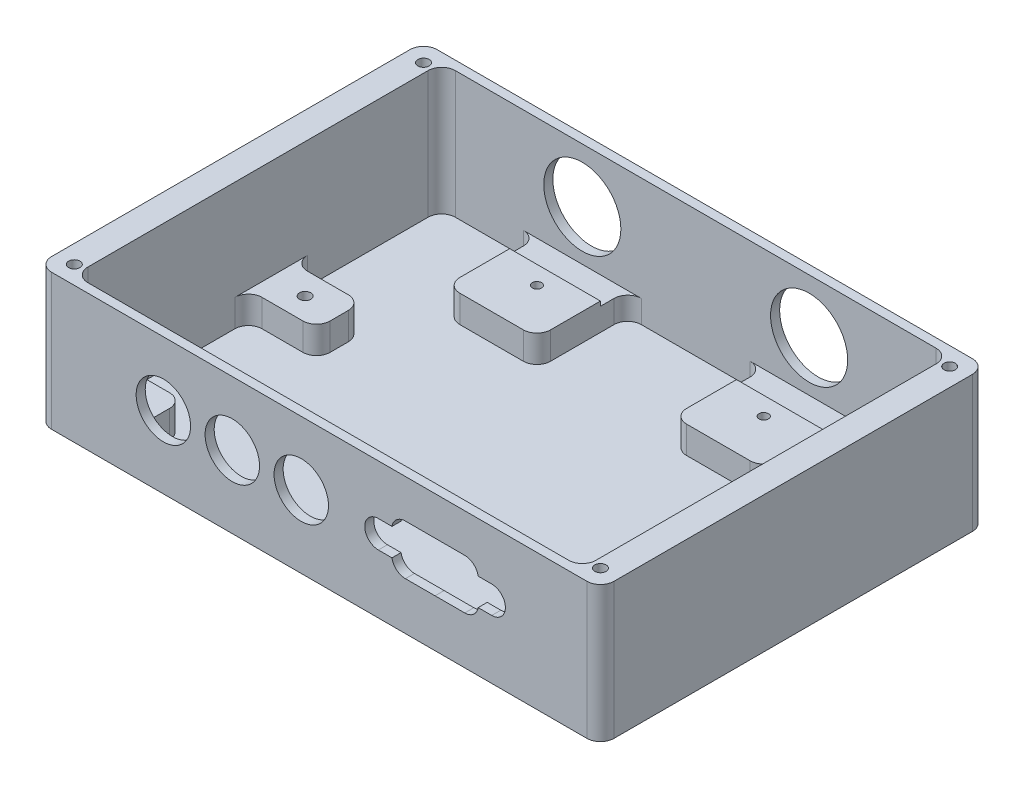
SolidWorks part; units mm, degrees
ref_plane "Ebene vorne" through (0, 0, 0) normal (0, 0, 1) x (1, 0, 0)
ref_plane "Ebene oben" through (0, 0, 0) normal (0, 1, 0) x (1, 0, 0)
ref_plane "Ebene rechts" through (0, 0, 0) normal (1, 0, 0) x (0, 0, -1)
sketch "Skizze1" plane through (0, 0, 0) normal (0, 1, 0) x (1, 0, 0)
  line L1 (0, 0) -> (116, 0)
  line L2 (0, 0) -> (0, 85)
  line L3 (0, 85) -> (116, 85)
  line L4 (116, 0) -> (116, 85)
  dimension "D1" = 85
  dimension "D2" = 116
extrude "Aufsatz-Linear austragen1" add sketch "Skizze1" along normal blind 30
shell "Schale1" thickness 2
sketch "Skizze2" plane through (0, 0, 0) normal (0, 0, 1) x (1, 0, 0)
  line L0 (4.8493, 15.94) -> (121.4088, 15.94) construction
  line L1 (0, 0) -> (116, 0) construction
  line L2 (0, 30) -> (0, 0) construction
  circle A0 centre (23.64, 15.94) radius 6
  circle A1 centre (38.84, 15.94) radius 6
  circle A2 centre (54.04, 15.94) radius 6
  dimension "D2" = 12
  dimension "D3" = 23.64
  dimension "D4" = 38.84
  dimension "D5" = 54.04
  dimension "D8" = 12
  dimension "D9" = 12
  dimension "D1" = 15.94
extrude "Schnitt-Linear austragen1" cut sketch "Skizze2" against normal blind 30
sketch "Skizze3" plane through (0, 0, 0) normal (0, 0, 1) x (1, 0, 0)
  line L0 (83.5402, 21.49) -> (76.9981, 21.49)
  line L1 (74.0401, 18.99) -> (71.04, 18.99)
  line L2 (0, 30) -> (0, 0) construction
  line L3 (68.04, 15.99) -> (134.747, 15.99) construction
  line L5 (83.5399, 11.9127) -> (83.5402, 21.49) construction
  line L7 (83.5402, 10.49) -> (76.9981, 10.49)
  line L8 (74.0401, 12.99) -> (71.04, 12.99)
  line L9 (83.5395, 10.49) -> (90.0816, 10.4896)
  line L10 (83.5402, 21.49) -> (90.0822, 21.4896)
  line L11 (93.0398, 12.9895) -> (96.0398, 12.9893)
  line L12 (93.0401, 18.9895) -> (96.0402, 18.9893)
  arc A0 (76.9981, 21.49) -> (74.0401, 18.99) centre (76.9981, 18.49) ccw
  arc A1 (71.04, 18.99) -> (71.04, 12.99) centre (71.04, 15.99) ccw
  arc A2 (76.9981, 10.49) -> (74.0401, 12.99) centre (76.9981, 13.49) cw
  arc A3 (90.0816, 10.4896) -> (93.0398, 12.9895) centre (90.0817, 13.4896) ccw
  arc A4 (96.0402, 18.9893) -> (96.0398, 12.9893) centre (96.04, 15.9893) cw
  arc A5 (90.0822, 21.4896) -> (93.0401, 18.9895) centre (90.082, 18.4896) cw
  point P12 (68.04, 15.99)
  dimension "D7" = 3
  dimension "D1" = 5.5
  dimension "D2" = 9.5
  dimension "D3" = 3
  dimension "D4" = 15.99
  dimension "D5" = 68.04
  dimension "D6" = 15.5
extrude "Schnitt-Linear austragen2" cut sketch "Skizze3" against normal blind 10 contours A5 L10 L0 A0 L1 A1 L8 A2 L7 L9 A3 L11 A4 L12
fillet "Verrundung1" radius 3 8 edges at (0, 15, -85) (116, 15, -85) (116, 15, 0) (0, 15, 0) (114, 16, -2) (114, 16, -83) (2, 16, -83) (2, 16, -2)
sketch "Skizze4" plane through (0, 2, 0) normal (0, 1, 0) x (1, 0, 0)
  line L0 (2, 12) -> (13, 12)
  line L1 (2, 80) -> (2, 5) construction
  line L2 (16, 9) -> (16, 2)
  line L3 (5, 2) -> (111, 2) construction
  line L5 (5, 2) -> (16, 2)
  line L6 (2, 12) -> (2, 5)
  line L7 (58, 0) -> (58, 20.7722) construction
  line L8 (3, 0) -> (113, 0) construction
  line L9 (114, 12) -> (114, 5)
  line L10 (111, 2) -> (100, 2)
  line L11 (100, 9) -> (100, 2)
  line L12 (114, 12) -> (103, 12)
  arc A1 (13, 12) -> (16, 9) centre (13, 9) cw
  arc A2 (2, 5) -> (5, 2) centre (5, 5) ccw construction
  arc A3 (2, 5) -> (5, 2) centre (5, 5) ccw
  arc A4 (114, 5) -> (111, 2) centre (111, 5) cw
  arc A5 (103, 12) -> (100, 9) centre (103, 9) ccw
  point P13 (16, 12)
  line M4 (5, 2) -> (111, 2)
  arc M5 (111, 2) -> (114, 5) centre (111, 5) ccw
  line M6 (114, 5) -> (114, 80)
  line M10 (2, 80) -> (2, 5)
  arc M11 (2, 5) -> (5, 2) centre (5, 5) ccw
  dimension "D5" = 3
  dimension "D3" = 14
  dimension "D4" = 10
extrude "Aufsatz-Linear austragen2" add sketch "Skizze4" along normal blind 6 contours A1 L0 L2 M10 M11 M4 | L12 A5 L11 M4 M5 M6
fillet "Verrundung2" radius 3 4 edges at (114, 5, -12) (100, 5, -2) (16, 5, -2) (2, 5, -12)
sketch "Skizze5" plane through (0, 2, 0) normal (0, 1, 0) x (1, 0, 0)
  line L0 (2, 80) -> (2, 5) construction
  line L1 (2, 50.4) -> (17, 50.4)
  line L2 (2, 50.4) -> (2, 40.4)
  line L3 (2, 40.4) -> (17, 40.4)
  line L4 (17, 50.4) -> (17, 40.4)
  line L5 (16, 7) -> (7.9271, 7) construction
  line L6 (16, 9) -> (16, 5) construction
  line L7 (17, 45.4) -> (7.9271, 45.4) construction
  line L8 (58, 0) -> (58, 60.7015) construction
  line L9 (3, 0) -> (113, 0) construction
  line L10 (99, 50.4) -> (99, 40.4)
  line L11 (114, 40.4) -> (99, 40.4)
  line L12 (114, 50.4) -> (114, 40.4)
  line L13 (114, 50.4) -> (99, 50.4)
  dimension "D1" = 38.4
  dimension "D2" = 10
  dimension "D3" = 15
extrude "Aufsatz-Linear austragen3" add sketch "Skizze5" along normal blind 6
fillet "Verrundung3" radius 3 8 edges at (114, 5, -40.4) (114, 5, -50.4) (99, 5, -40.4) (99, 5, -50.4) (2, 5, -50.4) (17, 5, -50.4) (17, 5, -40.4) (2, 5, -40.4)
sketch "Skizze6" plane through (0, 0, -85) normal (0, 0, -1) x (-1, 0, 0)
  line L0 (-128.5127, 18) -> (-8.2871, 18) construction
  line L1 (-113, 0) -> (-3, 0) construction
  line L2 (-58, 0) -> (-58, 33.8667) construction
  circle A0 centre (-83, 18) radius 8.5
  circle A1 centre (-33, 18) radius 8.5
  dimension "D2" = 17
  dimension "D3" = 50
  dimension "D1" = 18
extrude "Schnitt-Linear austragen3" cut sketch "Skizze6" against normal blind 5
sketch "Skizze7" plane through (0, 2, 0) normal (0, 1, 0) x (1, 0, 0)
  line L0 (58, 85) -> (58, 35.1088) construction
  line L1 (113, 85) -> (3, 85) construction
  line L2 (111, 83) -> (5, 83) construction
  line L3 (23, 63) -> (43, 63)
  line L4 (23, 63) -> (23, 83)
  line L5 (23, 83) -> (43, 83)
  line L6 (43, 63) -> (43, 83)
  line L7 (33, 63) -> (33, 71.5986) construction
  line L8 (0, 82) -> (0, 3) construction
  line L9 (23, 63) -> (23, 83)
  line L10 (43, 63) -> (43, 83)
  line L11 (93, 83) -> (73, 83)
  line L12 (73, 63) -> (73, 83)
  line L13 (93, 63) -> (73, 63)
  line L14 (93, 63) -> (93, 83)
  line M17 (111, 83) -> (5, 83)
  dimension "D1" = 33
  dimension "D2" = 20
  dimension "D3" = 20
extrude "Aufsatz-Linear austragen4" add sketch "Skizze7" along normal blind 6 contours L3 L6 L4 M17 | L13 L14 L12 M17
fillet "Verrundung4" radius 3 8 edges at (93, 5, -83) (93, 5, -63) (73, 5, -63) (73, 5, -83) (23, 5, -83) (23, 5, -63) (43, 5, -83) (43, 5, -63)
hole_wizard "M3 Gewindebohrung1" positions "Skizze8" profile "Skizze9" tap size "M3" standard "DIN"
sketch "Skizze8" plane through (0, 8, 0) normal (0, 1, 0) x (1, 0, 0)
  line L1 (106.5, 7.4) -> (9.5, 7.4) construction
  line L2 (106.5, 7.4) -> (106.5, 45.4) construction
  line L3 (106.5, 45.4) -> (9.5, 45.4) construction
  line L4 (9.5, 7.4) -> (9.5, 45.4) construction
  line L5 (19, 2) -> (97, 2) construction
  line L6 (114, 15) -> (114, 37.4) construction
  line L7 (58, 0) -> (58, 59.3993) construction
  line L8 (3, 0) -> (113, 0) construction
  point P1 (106.5, 7.4)
  point P2 (9.5, 45.4)
  point P117 (106.5, 45.4)
  point P118 (9.5, 7.4)
  dimension "D1" = 5.4
  dimension "D2" = 7.5
  dimension "D3" = 38
  dimension "D4" = 97
sketch "Skizze9" plane through (106.5, 8, -7.4) normal (1, 0, 0) x (0, 0, 1)
  line L0 (0, 0) -> (0, 9.2511)
  line L1 (0, 9.2511) -> (1.25, 8.5)
  line L2 (1.25, 8.5) -> (1.25, 0)
  line L5 (1.25, 0) -> (0, 0)
  line L10 (0, 9.2511) -> (-1.25, 8.5) construction
  line L11 (0, -6.35) -> (0, 107.95) construction
  dimension "Bohrerdurchmesser" = 2.5
  dimension "Bohrungstiefe" = 8.5
  dimension "Spitzenwinkel" = 118
cosmetic thread "Bohrungsgewinde4" parameters "D1"=6, "D2"=3
cosmetic thread "Bohrungsgewinde7" parameters "D1"=6, "D2"=3
cosmetic thread "Bohrungsgewinde9" parameters "D1"=6, "D2"=3
cosmetic thread "Bohrungsgewinde10" parameters "D1"=6, "D2"=3
hole_wizard "M2.5 Gewindebohrung1" positions "Skizze10" profile "Skizze11" tap size "M2.5" standard "DIN"
sketch "Skizze10" plane through (0, 8, 0) normal (0, 1, 0) x (1, 0, 0)
  line L0 (83, 63) -> (83, 83) construction
  line L1 (90, 63) -> (76, 63) construction
  line L2 (33, 63) -> (33, 83) construction
  line L3 (26, 63) -> (40, 63) construction
  line L4 (96, 83) -> (70, 83) construction
  point P10 (83, 73)
  point P12 (33, 73)
  dimension "D1" = 10
sketch "Skizze11" plane through (33, 8, -73) normal (1, 0, 0) x (0, 0, 1)
  line L0 (0, 0) -> (0, 7.8659)
  line L1 (0, 7.8659) -> (1.025, 7.25)
  line L2 (1.025, 7.25) -> (1.025, 0)
  line L5 (1.025, 0) -> (0, 0)
  line L10 (0, 7.8659) -> (-1.025, 7.25) construction
  line L11 (0, -6.35) -> (0, 107.95) construction
  dimension "Bohrerdurchmesser" = 2.05
  dimension "Bohrungstiefe" = 7.25
  dimension "Spitzenwinkel" = 118
cosmetic thread "Bohrungsgewinde5" parameters "D1"=5, "D2"=2.5
cosmetic thread "Bohrungsgewinde6" parameters "D1"=5, "D2"=2.5
sketch "Skizze12" plane through (0, 8, 0) normal (0, 1, 0) x (1, 0, 0)
  line L0 (111, 83) -> (96, 83) construction
  line L1 (108.8489, 83) -> (18.8489, 83)
  line L2 (108.8489, 83) -> (108.8489, 77)
  line L3 (108.8489, 77) -> (18.8489, 77)
  line L4 (18.8489, 83) -> (18.8489, 77)
  dimension "D1" = 6
  dimension "D2" = 90
extrude "Schnitt-Linear austragen4" cut sketch "Skizze12" against normal blind 1
sketch "Skizze13" plane through (0, 2, 0) normal (0, 1, 0) x (1, 0, 0)
  line L0 (119.1739, 25) -> (-5.709, 25) construction
  line L1 (58, 0) -> (58, 42.5667) construction
  line L2 (3, 0) -> (113, 0) construction
  circle A0 centre (88, 25) radius 3.2
  circle A1 centre (28, 25) radius 3.2
  dimension "D2" = 6.4
  dimension "D3" = 30
  dimension "D1" = 25
extrude "Schnitt-Linear austragen5" cut sketch "Skizze13" against normal blind 10
sketch "Skizze14" plane through (0, 0, 0) normal (0, -1, 0) x (-1, 0, 0)
  line L0 (-116, 3) -> (-116, 82) construction
  line L1 (-116, 0) -> (-120, 0)
  line L2 (-116, 3) -> (-116, 82)
  line L3 (-116, 85) -> (-120, 85)
  line L4 (-120, 0) -> (-120, 85)
  line L5 (0, 85) -> (4, 85)
  line L6 (0, 82) -> (0, 3)
  line L7 (0, 0) -> (4, 0)
  line L8 (4, 85) -> (4, 0)
  line L9 (0, 82) -> (0, 3) construction
  line L10 (-113, 85) -> (-116, 85)
  line L11 (-113, 0) -> (-116, 0)
  line L12 (-3, 0) -> (-113, 0) construction
  line L13 (0, 85) -> (-3, 85)
  line L14 (0, 0) -> (-3, 0)
  arc A0 (-113, 85) -> (-116, 82) centre (-113, 82) ccw
  arc A1 (-116, 3) -> (-113, 0) centre (-113, 3) ccw
  arc A2 (-3, 0) -> (0, 3) centre (-3, 3) ccw
  arc A3 (-3, 0) -> (0, 3) centre (-3, 3) ccw construction
  arc A4 (-3, 85) -> (0, 82) centre (-3, 82) cw
  arc A5 (0, 82) -> (-3, 85) centre (-3, 82) ccw construction
  dimension "D1" = 4
  dimension "D2" = 4
extrude "Aufsatz-Linear austragen5" add sketch "Skizze14" against normal up to surface (30 mm away) up to face at (58, 30, -42.5)
fillet "Verrundung5" radius 3 4 edges at (-4, 15, -85) (-4, 15, 0) (120, 15, -85) (120, 15, 0)
hole_wizard "M3 Gewindebohrung2" positions "Skizze15" profile "Skizze16" tap size "M3" standard "DIN"
sketch "Skizze15" plane through (0, 30, 0) normal (0, 1, 0) x (1, 0, 0)
  line L1 (0, 4) -> (116, 4) construction
  line L2 (0, 4) -> (0, 81) construction
  line L3 (0, 81) -> (116, 81) construction
  line L4 (116, 4) -> (116, 81) construction
  line L5 (117, 85) -> (-1, 85) construction
  line L6 (-1, 0) -> (117, 0) construction
  line L7 (120, 3) -> (120, 82) construction
  line L8 (-4, 82) -> (-4, 3) construction
  point P0 (0, 4)
  point P1 (116, 81)
  point P106 (0, 81)
  point P107 (116, 4)
  dimension "D1" = 4
  dimension "D2" = 4
  dimension "D3" = 4
  dimension "D4" = 4
sketch "Skizze16" plane through (0, 30, -4) normal (1, 0, 0) x (0, 0, 1)
  line L0 (0, 0) -> (0, 9.2511)
  line L1 (0, 9.2511) -> (1.25, 8.5)
  line L2 (1.25, 8.5) -> (1.25, 0)
  line L5 (1.25, 0) -> (0, 0)
  line L10 (0, 9.2511) -> (-1.25, 8.5) construction
  line L11 (0, -6.35) -> (0, 107.95) construction
  dimension "Bohrerdurchmesser" = 2.5
  dimension "Bohrungstiefe" = 8.5
  dimension "Spitzenwinkel" = 118
cosmetic thread "Bohrungsgewinde11" parameters "D1"=6, "D2"=3
cosmetic thread "Bohrungsgewinde12" parameters "D1"=6, "D2"=3
cosmetic thread "Bohrungsgewinde13" parameters "D1"=6, "D2"=3
cosmetic thread "Bohrungsgewinde14" parameters "D1"=6, "D2"=3
